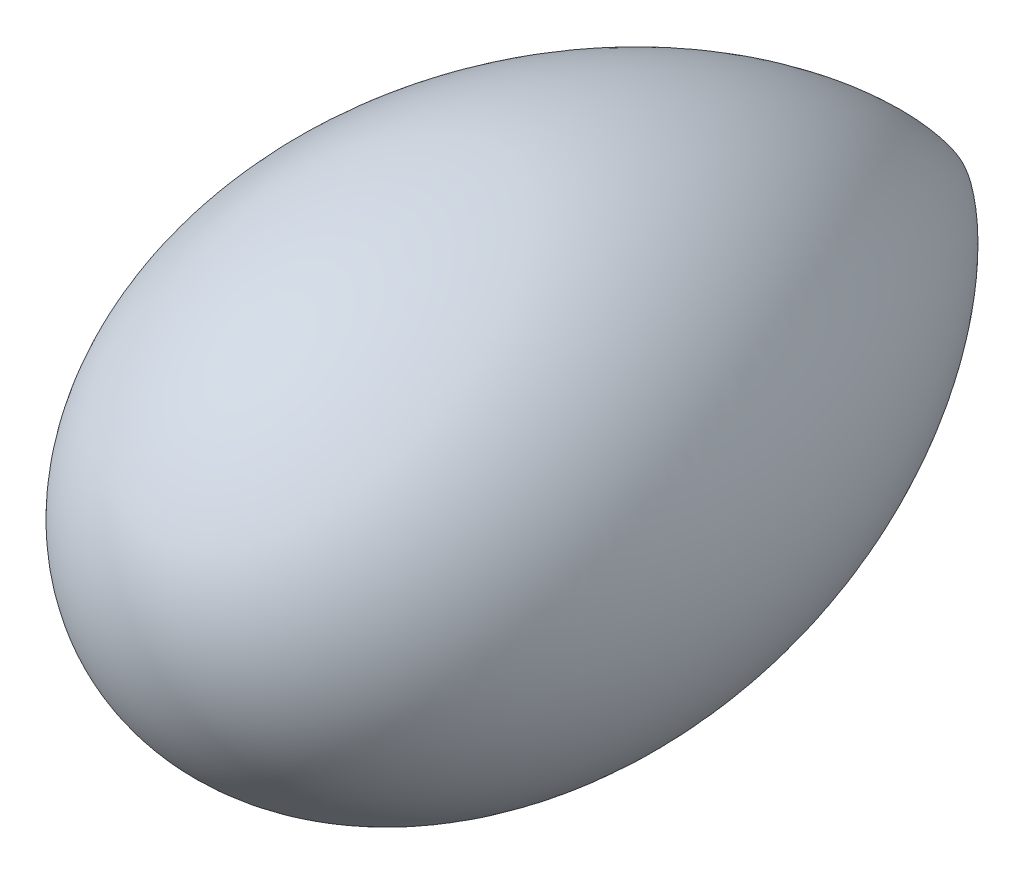
SolidWorks part; units mm, degrees
ref_plane "Front Plane" through (0, 0, 0) normal (0, 0, 1) x (1, 0, 0)
ref_plane "Top Plane" through (0, 0, 0) normal (0, 1, 0) x (1, 0, 0)
ref_plane "Right Plane" through (0, 0, 0) normal (1, 0, 0) x (0, 0, -1)
sketch "Sketch1" plane through (0, 0, 0) normal (0, 1, 0) x (1, 0, 0)
  line L0 (0, 0) -> (0, -55.7313) construction
  line L1 (0, -55.7313) -> (0, 0)
  spline S0 degree 4 poles (-6.2544, -54.1334) (-6.133, -54.198) (-5.8887, -54.324) (-5.5175, -54.5038) (-5.0137, -54.724) (-4.5037, -54.9234) (-3.9885, -55.1014) (-3.3393, -55.2967) (-2.683, -55.4561) (-2.0181, -55.579) (-1.4158, -55.656) (-1.0109, -55.6931) (-0.6774, -55.7146) (-0.4049, -55.726) (-0.1143, -55.7317) (0.1068, -55.7318) (0.3909, -55.7264) (0.6566, -55.7156) (0.9794, -55.6955) (1.3717, -55.6606) (1.7609, -55.6124) (2.1487, -55.551) (2.5346, -55.4793) (3.1744, -55.3425) (4.1209, -55.0799) (5.2246, -54.6623) (6.3979, -54.0796) (7.4064, -53.47) (8.2639, -52.8686) (9.0804, -52.2127) (9.8546, -51.5074) (10.7684, -50.5702) (11.7779, -49.3655) (12.7394, -47.9894) (13.6311, -46.4448) (14.4102, -44.8411) (15.0797, -43.1884) (15.841, -40.8458) (16.5179, -37.7735) (16.9086, -34.1217) (16.8566, -29.9265) (16.346, -25.7634) (15.4096, -21.6758) (14.0734, -17.7012) (12.3574, -13.8754) (10.2758, -10.2352) (8.1409, -7.2504) (6.0863, -4.8705) (4.3558, -3.1712) (3.0659, -2.0508) (1.9745, -1.2151) (1.1937, -0.6807) (0.5875, -0.3105) (0.2554, -0.126) (0.0858, -0.0407) (0, 0) knots 0 0 0 0 0 0.007194 0.014388 0.021582 0.028776 0.035845 0.042913 0.05705 0.064119 0.071188 0.074722 0.078256 0.08179 0.085325 0.088749 0.092172 0.095596 0.09902 0.105868 0.112716 0.11614 0.119563 0.126411 0.146955 0.167498 0.181193 0.194889 0.208584 0.22228 0.235976 0.249671 0.277062 0.304453 0.323693 0.342933 0.370324 0.397715 0.452497 0.507279 0.562062 0.616844 0.671626 0.726408 0.78119 0.835973 0.890755 0.918146 0.945537 0.96283 0.980124 0.990062 0.995031 1 1 1 1 1 construction
  spline S1 degree 4 poles (0, -55.7313) (0.0598, -55.7313) (0.1796, -55.7304) (0.3909, -55.7264) (0.6566, -55.7156) (0.9794, -55.6955) (1.3717, -55.6606) (1.7609, -55.6124) (2.1487, -55.551) (2.5346, -55.4793) (3.1744, -55.3425) (4.1209, -55.0799) (5.2246, -54.6623) (6.3979, -54.0796) (7.4064, -53.47) (8.2639, -52.8686) (9.0804, -52.2127) (9.8546, -51.5074) (10.7684, -50.5702) (11.7779, -49.3655) (12.7394, -47.9894) (13.6311, -46.4448) (14.4102, -44.8411) (15.0797, -43.1884) (15.841, -40.8458) (16.5179, -37.7735) (16.9086, -34.1217) (16.8566, -29.9265) (16.346, -25.7634) (15.4096, -21.6758) (14.0734, -17.7012) (12.3574, -13.8754) (10.2758, -10.2352) (8.1409, -7.2504) (6.0863, -4.8705) (4.3558, -3.1712) (3.0659, -2.0508) (1.9745, -1.2151) (1.1937, -0.6807) (0.5875, -0.3105) (0.2554, -0.126) (0.0858, -0.0407) (0, 0) knots 0.085325 0.085325 0.085325 0.085325 0.085325 0.088749 0.092172 0.095596 0.09902 0.105868 0.112716 0.11614 0.119563 0.126411 0.146955 0.167498 0.181193 0.194889 0.208584 0.22228 0.235976 0.249671 0.277062 0.304453 0.323693 0.342933 0.370324 0.397715 0.452497 0.507279 0.562062 0.616844 0.671626 0.726408 0.78119 0.835973 0.890755 0.918146 0.945537 0.96283 0.980124 0.990062 0.995031 1 1 1 1 1
revolve "Revolve1" add sketch "Sketch1" angle 360 about L0
